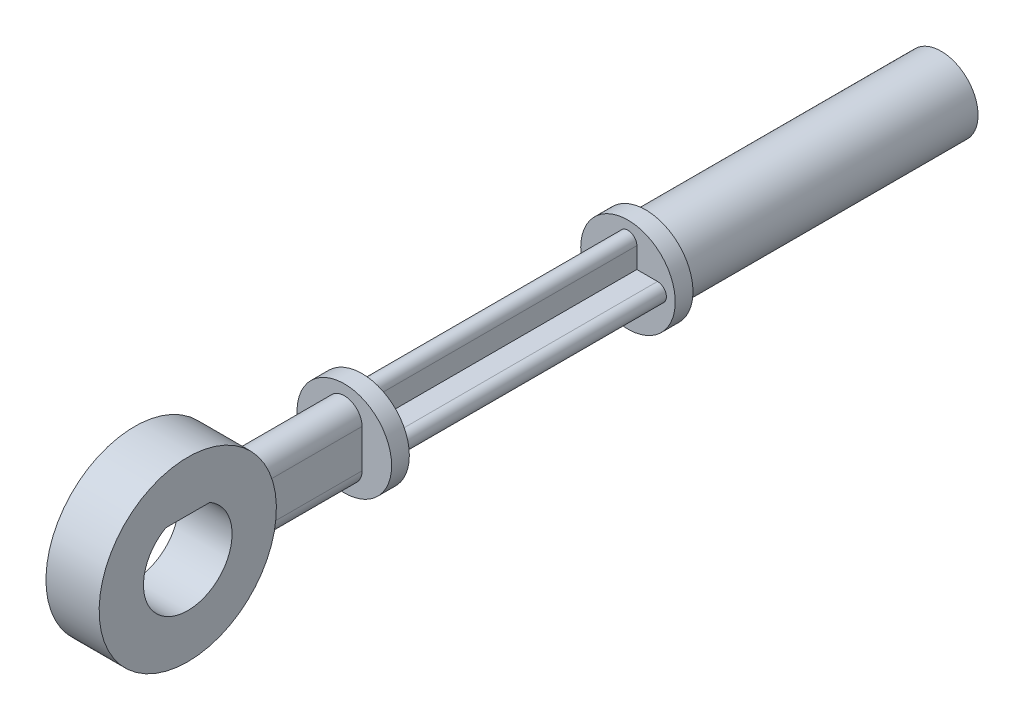
SolidWorks part; units mm, degrees
ref_plane "Front" through (0, 0, 0) normal (0, 0, 1) x (1, 0, 0)
ref_plane "Top" through (0, 0, 0) normal (0, 1, 0) x (1, 0, 0)
ref_plane "Right" through (0, 0, 0) normal (1, 0, 0) x (0, 0, -1)
sketch "Sketch1" plane through (0, 0, 0) normal (0, 0, 1) x (1, 0, 0)
  circle A0 centre (0, 0) radius 16
  dimension "D1" = 32
extrude "Base-Extrude" add sketch "Sketch1" along normal mid plane 6
sketch "Sketch2" plane through (0, 0, 3) normal (0, 0, 1) x (1, 0, 0)
  line L0 (-6, -6.5) -> (-6, 6.5)
  line L1 (6, 6.5) -> (6, -6.5)
  line L2 (0, -6.5) -> (0, 6.5) construction
  arc A0 (-6, 6.5) -> (6, 6.5) centre (0, 6.5) cw
  arc A1 (6, -6.5) -> (-6, -6.5) centre (0, -6.5) cw
  dimension "D1" = 6
  dimension "D2" = 25
ref_plane "Plane1" through (0, 0, 65) normal (0, 0, 1) x (1, 0, 0)
extrude "Extrude3" add sketch "Sketch2" along normal up to surface (62 mm away) up to plane "Plane1"
sketch "Sketch5" plane through (0, 0, -3) normal (0, 0, -1) x (-1, 0, 0)
  line L0 (-3, 3) -> (-3, 10)
  line L1 (3, 10) -> (3, 3)
  line L2 (3, 3) -> (10, 3)
  line L3 (10, -3) -> (3, -3)
  line L4 (3, -3) -> (3, -10)
  line L5 (-3, -10) -> (-3, -3)
  line L6 (-3, -3) -> (-10, -3)
  line L7 (-10, 3) -> (-3, 3)
  line L8 (-10, 0) -> (10, 0) construction
  line L9 (0, 10) -> (0, -10) construction
  arc A0 (-3, 10) -> (3, 10) centre (0, 10) cw
  arc A1 (10, 3) -> (10, -3) centre (10, 0) cw
  arc A2 (3, -10) -> (-3, -10) centre (0, -10) cw
  arc A3 (-10, -3) -> (-10, 3) centre (-10, 0) cw
  dimension "D1" = 26
  dimension "D3" = 26
  dimension "D2" = 6
extrude "Boss-Extrude1" add sketch "Sketch5" along normal blind 90
sketch "Sketch6" plane through (0, 0, -93) normal (0, 0, -1) x (-1, 0, 0)
  circle A0 centre (0, 0) radius 16 construction
  circle A1 centre (0, 0) radius 16
extrude "Boss-Extrude2" add sketch "Sketch6" along normal blind 6
sketch "Sketch7" plane through (0, 0, -99) normal (0, 0, -1) x (-1, 0, 0)
  circle A0 centre (0, 0) radius 12.5
  point P3 (12.5, 0)
  dimension "D1" = 25
sketch "Sketch9" plane through (0, 0, 65) normal (0, 0, 1) x (1, 0, 0)
  line L1 (-9, 30) -> (9, 30)
  line L2 (9, 30) -> (9, 0)
  line L4 (9, 0) -> (-9, 0)
  line L5 (-9, 0) -> (-9, 30)
  line L6 (9, 0) -> (54.9339, 0) construction
  dimension "D1" = 60
  dimension "D2" = 18
revolve "Boss-Revolve1" add sketch "Sketch9" angle 360 about L6
sketch "Sketch10" plane through (9, 0, 0) normal (1, 0, 0) x (0, 0, -1)
  line L0 (-72.4833, 13) -> (-57.5167, 13)
  arc A0 (-72.4833, 13) -> (-57.5167, 13) centre (-65, 0) ccw
  dimension "D1" = 30
  dimension "D2" = 28
extrude "Cut-Extrude1" cut sketch "Sketch10" against normal through all
extrude "Extrude4" add sketch "Sketch7" along normal blind 100
